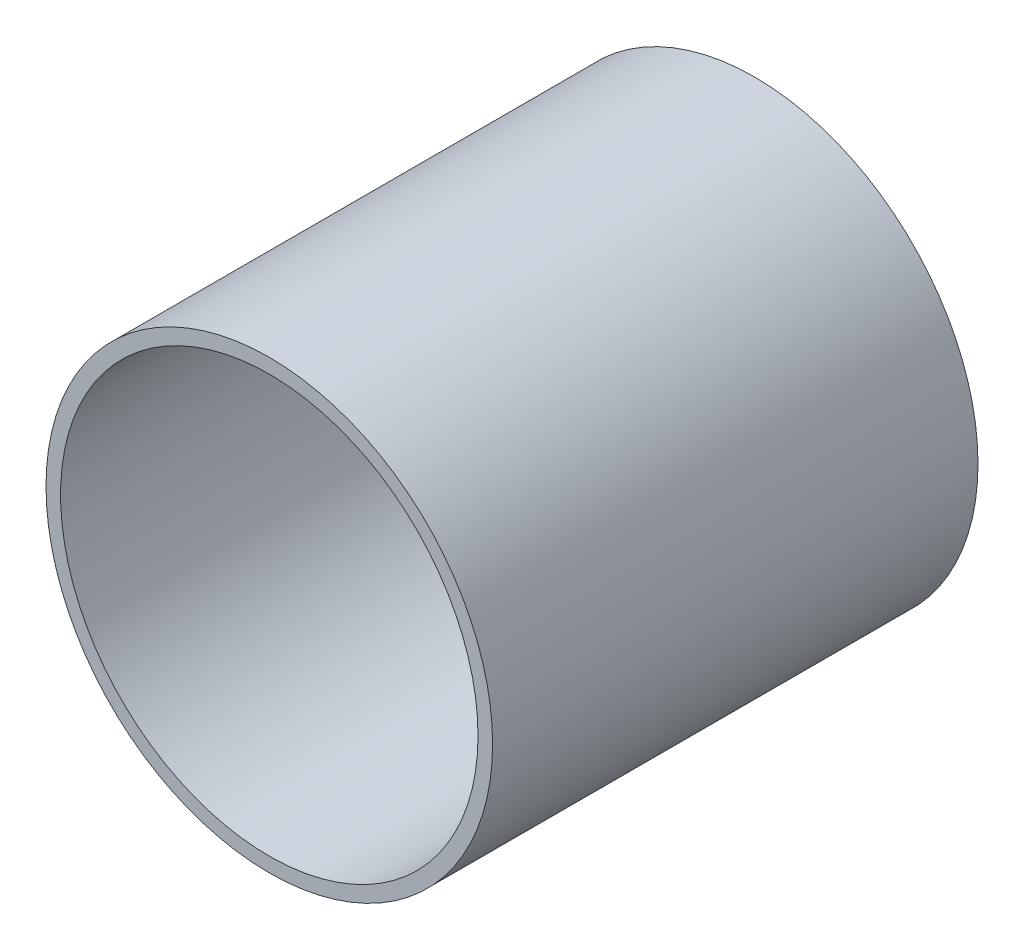
SolidWorks part; units mm, degrees
ref_plane "前视基准面" through (0, 0, 0) normal (0, 0, 1) x (1, 0, 0)
ref_plane "上视基准面" through (0, 0, 0) normal (0, 1, 0) x (1, 0, 0)
ref_plane "右视基准面" through (0, 0, 0) normal (1, 0, 0) x (0, 0, -1)
sketch "草图1" plane through (0, 0, 0) normal (0, 0, 1) x (1, 0, 0)
  circle A0 centre (0, 0) radius 23
  circle A1 centre (0, 0) radius 21.5
  dimension "D1" = 46
  dimension "D2" = 43
extrude "凸台-拉伸1" add sketch "草图1" along normal blind 50
